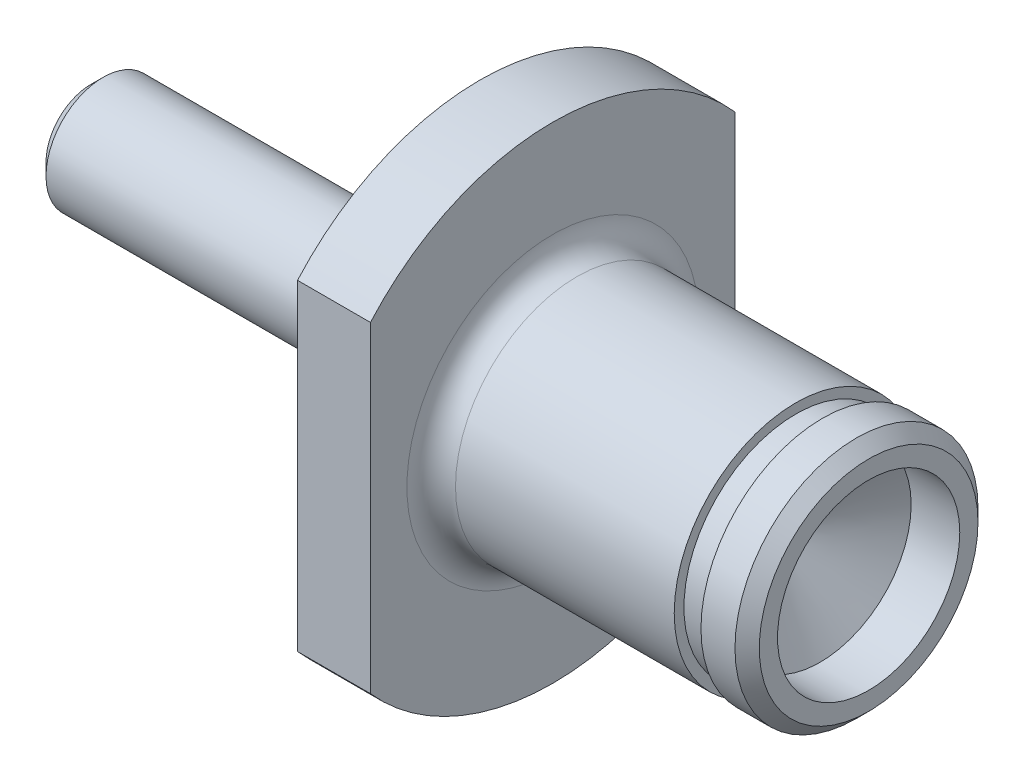
SolidWorks part; units mm, degrees
ref_plane "Płaszczyzna przednia" through (0, 0, 0) normal (0, 0, 1) x (1, 0, 0)
ref_plane "Płaszczyzna górna" through (0, 0, 0) normal (0, 1, 0) x (1, 0, 0)
ref_plane "Płaszczyzna prawa" through (0, 0, 0) normal (1, 0, 0) x (0, 0, -1)
sketch "Szkic1" plane through (0, 0, 0) normal (0, 0, 1) x (1, 0, 0)
  line L0 (0, 0) -> (0, 2.35)
  line L1 (0, 2.35) -> (16, 2.35)
  line L2 (16, 2.35) -> (16, 10)
  line L3 (16, 10) -> (19, 10)
  line L4 (19, 10) -> (19, 5)
  line L6 (32, 5) -> (32, 0)
  line L7 (32, 0) -> (0, 0)
  line L8 (0, 0) -> (-7.7295, 0) construction
  line L10 (19, 5) -> (29, 5)
  line L11 (29, 5) -> (29, 4.6)
  line L12 (29, 4.6) -> (30.1, 4.6)
  line L13 (30.1, 4.6) -> (30.1, 5)
  line L14 (30.1, 5) -> (32, 5)
  dimension "D1" = 16
  dimension "D2" = 20
  dimension "D3" = 4.7
  dimension "D4" = 3
  dimension "D5" = 1.1
  dimension "D6" = 32
  dimension "D7" = 10
  dimension "D8" = 0.4
  dimension "D9" = 10
revolve "Obrót1" add sketch "Szkic1" angle 360 about L8
cosmetic thread "Oznaczenie gwintu1" parameters "D2"=4.4
chamfer "Sfazowanie1" distance 0.5 angle 45 1 edges at (0, 0, -2.35)
fillet "Zaokrąglenie1" radius 0.5 1 edges at (16, 0, -2.35)
hole_wizard "Otwory ustalające Ø8.0mm1" positions "Szkic2" profile "Szkic4" hole size "Ø8.0" standard "Ansi Metric"
sketch "Szkic2" plane through (32, 0, 0) normal (1, 0, 0) x (0, 0, -1)
  point P0 (0, 0)
sketch "Szkic4" plane through (32, 0, 0) normal (0, 1, 0) x (0, 0, -1)
  line L0 (0, 0) -> (0, 4.2532)
  line L1 (0, 4.2532) -> (3.75, 2)
  line L2 (3.75, 2) -> (3.75, 0)
  line L5 (3.75, 0) -> (0, 0)
  line L10 (0, 4.2532) -> (-3.75, 2) construction
  line L11 (0, -6.35) -> (0, 107.95) construction
  dimension "Średnica otworu" = 7.5
  dimension "Głębokość otworu" = 2
  dimension "Kąt wiertła" = 118
fillet "Zaokrąglenie2" radius 1 1 edges at (19, 0, -5)
chamfer "Sfazowanie2" distance 0.5 angle 45 1 edges at (32, 0, -5)
sketch "Szkic5" plane through (19, 0, 0) normal (1, 0, 0) x (0, 0, -1)
  line L0 (-7.5, -6.6144) -> (-7.5, 6.6144)
  line L1 (7.5, -6.6144) -> (7.5, 6.6144)
  line L2 (0, 0) -> (0, 11.3222) construction
  circle A0 centre (0, 0) radius 10 construction
  arc A1 (7.5, -6.6144) -> (7.5, 6.6144) centre (0, 0) ccw
  arc A2 (0, 10) -> (-7.5, -6.6144) centre (0, 0) ccw
  circle M5 centre (0, 0) radius 10
  dimension "D1" = 15
extrude "Wytnij-wyciągnięcie1" cut sketch "Szkic5" against normal up to surface (3 mm away) contours L1 M5 | L0 M5 up to face at (16, 0, 2.85)
